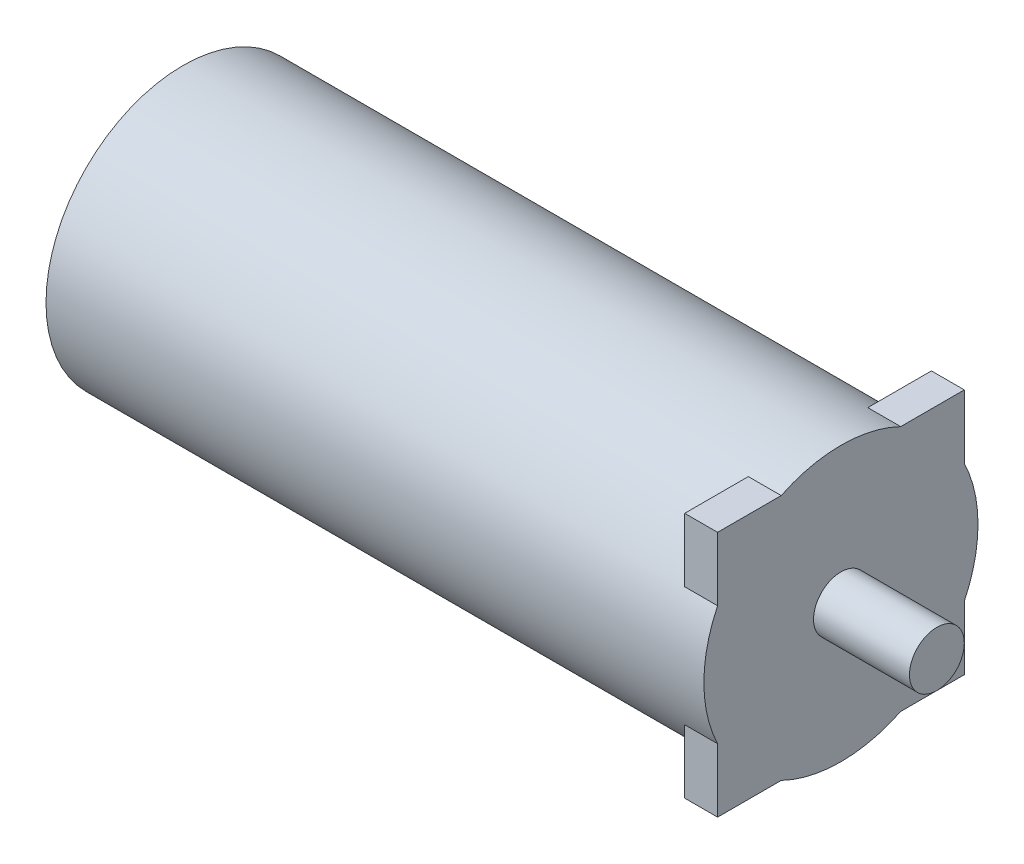
SolidWorks part; units mm, degrees
ref_plane "Front Plane" through (0, 0, 0) normal (1, 0, 0) x (0, 1, 0)
ref_plane "Top Plane" through (0, 0, 0) normal (0, 0, 1) x (0, 1, 0)
ref_plane "Right Plane" through (0, 0, 0) normal (0, 1, 0) x (-1, 0, 0)
sketch "Sketch1" plane through (0, 0, 0) normal (1, 0, 0) x (0, 1, 0)
  line L1 (-45, 45) -> (45, 45)
  line L2 (-45, 45) -> (-45, -45)
  line L3 (-45, -45) -> (45, -45)
  line L4 (45, 45) -> (45, -45)
  point P4 (0, 0)
  point P5 (0, 45)
  point P6 (-45, 0)
  dimension "D1" = 90
  dimension "D2" = 90
  dimension "D3" = 45
extrude "Boss-Extrude1" add sketch "Sketch1" against normal blind 12 contours L4 L3 L2 L1
sketch "Sketch2" plane through (0, 0, 0) normal (1, 0, 0) x (0, 1, 0)
  circle A0 centre (0, 0) radius 50
  dimension "D1" = 100
extrude "Boss-Extrude2" add sketch "Sketch2" against normal blind 240 contours A0
sketch "Sketch3" plane through (0, 0, 0) normal (1, 0, 0) x (0, 0, -1)
  circle A0 centre (0, 0) radius 10
  dimension "D1" = 20
extrude "Boss-Extrude3" add sketch "Sketch3" along normal blind 35 contours A0
